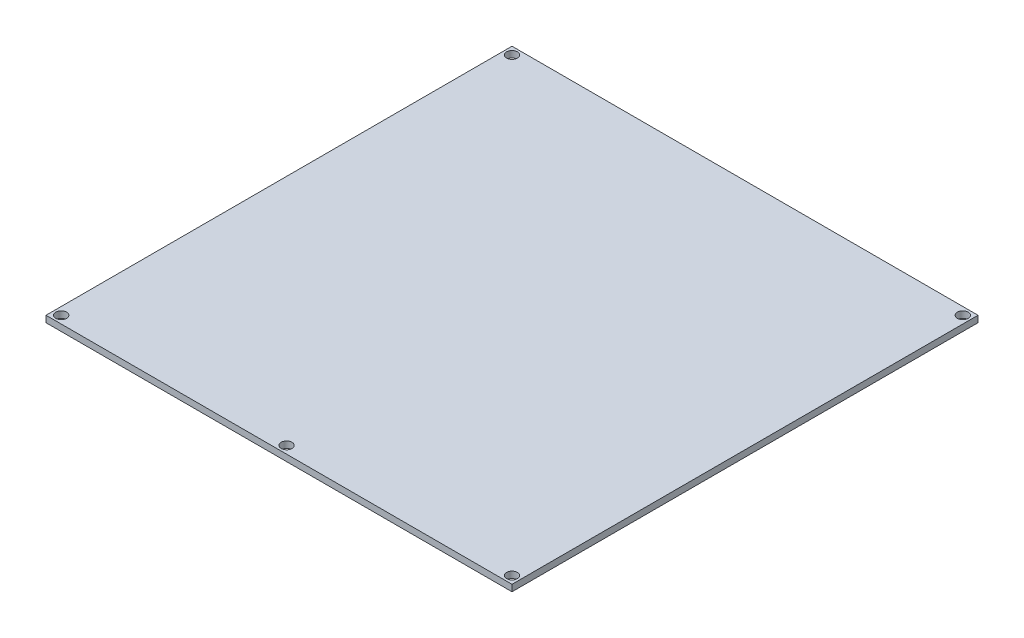
SolidWorks part; units mm, degrees
ref_plane "Front Plane" through (0, 0, 0) normal (0, 0, 1) x (1, 0, 0)
ref_plane "Top Plane" through (0, 0, 0) normal (0, 1, 0) x (1, 0, 0)
ref_plane "Right Plane" through (0, 0, 0) normal (1, 0, 0) x (0, 0, -1)
sketch "Sketch1" plane through (0, 0, 0) normal (0, 1, 0) x (1, 0, 0)
  line L1 (0, 0) -> (215, 0)
  line L2 (0, 0) -> (0, 215)
  line L3 (0, 215) -> (215, 215)
  line L4 (215, 0) -> (215, 215)
  circle A0 centre (3.5, 211.5) radius 2.5
  circle A1 centre (3.5, 3.5) radius 2.5
  circle A2 centre (211.5, 3.5) radius 2.5
  circle A3 centre (211.5, 211.5) radius 2.5
  circle A4 centre (107.5, 3.5) radius 2.5
  dimension "D3" = 5
  dimension "D4" = 5
  dimension "D5" = 5
  dimension "D6" = 5
  dimension "D15" = 5
  dimension "D1" = 215
  dimension "D2" = 215
  dimension "D7" = 3.5
  dimension "D8" = 3.5
  dimension "D9" = 3.5
  dimension "D10" = 3.5
  dimension "D11" = 3.5
  dimension "D12" = 3.5
  dimension "D13" = 3.5
  dimension "D14" = 3.5
  dimension "D16" = 3.5
  dimension "D17" = 107.5
extrude "Boss-Extrude1" add sketch "Sketch1" along normal blind 3
